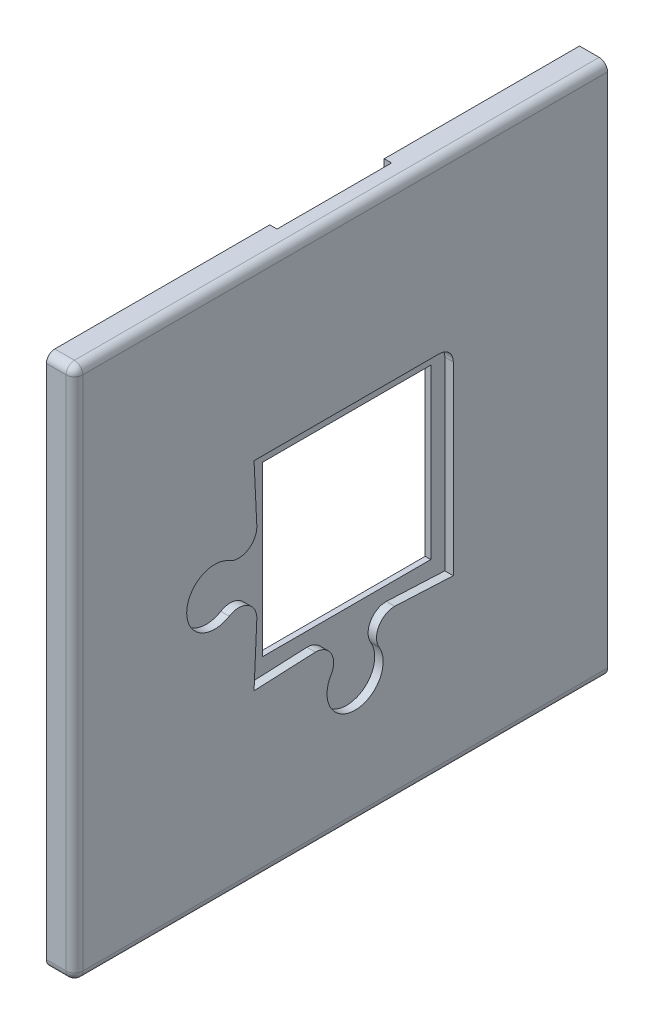
SolidWorks part; units mm, degrees
ref_plane "Front Plane" through (0, 0, 0) normal (0, 0, 1) x (1, 0, 0)
ref_plane "Top Plane" through (0, 0, 0) normal (0, 1, 0) x (1, 0, 0)
ref_plane "Right Plane" through (0, 0, 0) normal (1, 0, 0) x (0, 0, -1)
sketch "Sketch1" plane through (0, 0, 0) normal (1, 0, 0) x (0, 0, -1)
  line L1 (-100, 95) -> (90, 95)
  line L2 (-100, 95) -> (-100, -95)
  line L3 (-100, -95) -> (90, -95)
  line L4 (90, 95) -> (90, -95)
  point P6 (-100, 0)
  dimension "D1" = 190
  dimension "D2" = 190
  dimension "D3" = 100
extrude "Boss-Extrude1" add sketch "Sketch1" along normal blind 10
sketch "Sketch2" plane through (0, 0, 0) normal (-1, 0, 0) x (0, 0, 1)
  line L0 (-35.5, 35.5) -> (-25.5, 35.5)
  line L1 (-35.5, 35.5) -> (-25.5, 35.5)
  line L2 (-35.5, 35.5) -> (-35.5, -35.5)
  line L3 (-35.5, -35.5) -> (35.5, -35.5)
  line L4 (35.5, 35.5) -> (35.5, -35.5)
  line L5 (-25.5, 35.5) -> (-5, 44.5)
  line L6 (-5, 44.5) -> (5, 44.5)
  line L7 (5, 44.5) -> (25.5, 35.5)
  line L8 (25.5, 35.5) -> (35.5, 35.5)
  line L9 (25.5, 35.5) -> (35.5, 35.5)
  line L10 (36.5, 35.5) -> (36.5, -36.5)
  line L11 (-36.5, -36.5) -> (36.5, -36.5)
  line L12 (-36.5, 35.5) -> (-36.5, -36.5)
  line L13 (-35.5, 36.5) -> (-25.5, 36.5)
  line L14 (-25.902, 36.4156) -> (-5.2098, 45.5)
  line L15 (-5.2098, 45.5) -> (5.2098, 45.5)
  line L16 (5.2098, 45.5) -> (25.902, 36.4156)
  line L17 (25.5, 36.5) -> (35.5, 36.5)
  line L18 (-36.5, 35.5) -> (-36.5, 36.5)
  line L19 (-36.5, 36.5) -> (-35.5, 36.5)
  line L20 (35.5, 36.5) -> (36.5, 36.5)
  line L21 (36.5, 36.5) -> (36.5, 35.5)
  point P5 (0, -35.5)
  point P12 (35.5, 0)
  dimension "D1" = 10
  dimension "D2" = 71
  dimension "D3" = 71
  dimension "D4" = 10
  dimension "D5" = 10
  dimension "D6" = 80
  dimension "D7" = 20.5
  dimension "D8" = 1
extrude "Cut-Extrude1" cut sketch "Sketch2" against normal blind 5
sketch "Sketch3" plane through (5, 0, 0) normal (-1, 0, 0) x (0, 0, 1)
  line L1 (-30, 30) -> (30, 30)
  line L2 (-30, 30) -> (-30, -30)
  line L3 (-30, -30) -> (30, -30)
  line L4 (30, 30) -> (30, -30)
  point P4 (0, -30)
  point P6 (30, 0)
  dimension "D1" = 60
  dimension "D2" = 60
extrude "Cut-Extrude2" cut sketch "Sketch3" against normal through all
sketch "Sketch4" plane through (10, 0, 0) normal (1, 0, 0) x (0, 0, -1)
  line L2 (-35, 35) -> (-35, 14.1421) construction
  line L3 (-35, -35) -> (-14.1421, -35) construction
  line L8 (35, 30) -> (35, -35)
  line L9 (36, -36) -> (-36, -36) construction
  line L10 (-36, 37) -> (36, 37) construction
  line L11 (-36, 37) -> (-36, -36) construction
  line L13 (36, 37) -> (36, -36) construction
  line L14 (14.1421, -35) -> (35, -35) construction
  line L15 (30, 35) -> (-35, 35)
  line L16 (-35, -14.1421) -> (-35, -35) construction
  line L17 (-35, 14.1421) -> (-36, 35)
  line L18 (-36, 35) -> (-35, 35)
  line L19 (-14.1421, -35) -> (-36, -36)
  line L20 (-36, -36) -> (-35, -14.1421)
  line L21 (14.1421, -35) -> (35, -36)
  line L22 (35, -36) -> (35, -35)
  arc A6 (-8.571, -44.8485) -> (8.571, -44.8485) centre (0, -50) ccw
  arc A7 (14.1421, -35) -> (8.571, -44.8485) centre (14.1421, -41.5) ccw
  arc A8 (-8.571, -44.8485) -> (-14.1421, -35) centre (-14.1421, -41.5) ccw
  arc A9 (-44.8485, 8.571) -> (-35, 14.1421) centre (-41.5, 14.1421) ccw
  arc A10 (-35, -14.1421) -> (-44.8485, -8.571) centre (-41.5, -14.1421) ccw
  arc A11 (-44.8485, 8.571) -> (-44.8485, -8.571) centre (-50, 0) ccw
  arc A12 (30, 35) -> (35, 30) centre (30, 30) cw
  point P9 (35, 35)
  point P22 (0, 0)
  point P24 (0, 0)
  dimension "D3" = 2
  dimension "D4" = 2
  dimension "D6" = 15
  dimension "D8" = 1
  dimension "D9" = 1
  dimension "D12" = 20
  dimension "D13" = 13
  dimension "D14" = 13
  dimension "D7" = 20.8579
  dimension "D5" = 5
  dimension "D1" = 70
  dimension "D2" = 70
  dimension "D10" = 1
  dimension "D11" = 15
  dimension "D15" = 35
extrude "Cut-Extrude3" cut sketch "Sketch4" against normal blind 3
sketch "Sketch8" plane through (0, 0, 0) normal (-1, 0, 0) x (0, 0, 1)
  line L0 (20, 86) -> (-20, 86) construction
  line L1 (20.4, 98.695) -> (-20.4, 98.695)
  line L2 (20.4, 98.695) -> (20.4, 86.4)
  line L3 (20.4, 86.4) -> (-20.4, 86.4)
  line L4 (-20.4, 98.695) -> (-20.4, 86.4)
  dimension "D1" = 0.4
extrude "Cut-Extrude4" cut sketch "Sketch8" against normal blind 2.6
shell "Shell1" [suppressed] thickness 5
sketch "Sketch9" plane through (0, 0, 0) normal (-1, 0, 0) x (0, 0, 1)
  line L0 (-85, 90) -> (-85, -90)
  line L1 (-85, -90) -> (95, -90)
  line L2 (95, -90) -> (95, 90)
  line L3 (95, 90) -> (25.4, 90)
  line L4 (25.4, 90) -> (25.4, 81.4)
  line L5 (25.4, 81.4) -> (-25.4, 81.4)
  line L6 (-25.4, 81.4) -> (-25.4, 90)
  line L7 (-25.4, 90) -> (-85, 90)
  line L8 (-41.5, 41.5) -> (-41.5, -41.5)
  line L9 (-41.5, -41.5) -> (41.5, -41.5)
  line L10 (41.5, -41.5) -> (41.5, 41.5)
  line L14 (-90, -95) -> (-90, 95) construction
  line L15 (-90, 95) -> (-20.4, 95) construction
  line L16 (-20.4, 95) -> (-20.4, 86.4) construction
  line L17 (20.4, 86.4) -> (20.4, 95) construction
  line L18 (-20.4, 86.4) -> (20.4, 86.4) construction
  line L19 (100, 95) -> (100, -95) construction
  line L20 (100, -95) -> (-90, -95) construction
  line L21 (-36.5, -36.5) -> (-36.5, 36.5) construction
  line L22 (-36.5, -36.5) -> (36.5, -36.5) construction
  line L23 (36.5, 36.5) -> (36.5, -36.5) construction
  line L24 (-5.2098, 45.5) -> (5.2098, 45.5)
  line L27 (-41.5, 41.5) -> (-19.2962, 41.5)
  line L28 (-19.2962, 41.5) -> (-5.6295, 47.5)
  line L29 (-5.6295, 47.5) -> (5.6295, 47.5) construction
  line L30 (5.6295, 47.5) -> (19.2962, 41.5)
  line L32 (19.2962, 41.5) -> (41.5, 41.5)
  line L33 (-36.5, 36.5) -> (-25.7098, 36.5) construction
  line L35 (-25.7098, 36.5) -> (-5.2098, 45.5) construction
  line L36 (5.2098, 45.5) -> (25.7098, 36.5) construction
  line L37 (-5.2098, 45.5) -> (5.2098, 45.5) construction
  line L38 (5.2098, 45.5) -> (25.7098, 36.5) construction
  line L39 (25.7098, 36.5) -> (36.5, 36.5) construction
  line L40 (-25.7098, 36.5) -> (-5.2098, 45.5) construction
  line L41 (-12.5, -41.5) -> (-12.5, -61.5)
  line L42 (-12.5, -61.5) -> (12.5, -61.5)
  line L43 (12.5, -61.5) -> (12.5, -41.5)
  line L44 (41.5, 12.5) -> (61.5, 12.5)
  line L45 (61.5, 12.5) -> (61.5, -12.5)
  line L46 (61.5, -12.5) -> (41.5, -12.5)
  line L47 (-5.2098, 45.5) -> (-5.6295, 47.5)
  line L48 (5.2098, 45.5) -> (5.6295, 47.5)
  point P59 (61.5, 0)
  point P62 (41.5, 0)
  point P63 (0, -61.5)
  point P64 (0, -41.5)
  line M34 (-5.2098, 45.5) -> (5.2098, 45.5)
  dimension "D1" = 5
  dimension "D2" = 5
  dimension "D3" = 5
  dimension "D4" = 5
  dimension "D5" = 5
  dimension "D6" = 5
  dimension "D7" = 5
  dimension "D8" = 5
  dimension "D9" = 5
  dimension "D10" = 5
  dimension "D11" = 5
  dimension "D12" = 5
  dimension "D13" = 2
  dimension "D14" = 2
  dimension "D15" = 5
  dimension "D16" = 2
  dimension "D17" = 25
  dimension "D18" = 25
  dimension "D19" = 20
  dimension "D20" = 20
extrude "Cut-Extrude5" cut sketch "Sketch9" against normal blind 7 contours L6 L7 L0 L1 L2 L3 L4 L5 L45 L46 L10 L9 L43 L42 L41 L8 L27 L28 L29 L30 L32 L44 | L29 L47 L48 M34
fillet "Fillet1" radius 3 5 edges at (5, 95, 100) (5, -95, 100) (10, 95, 5) (10, 0, 100) (10, -95, 5)
sketch "Sketch10" plane through (0, -61.5, 0) normal (0, -1, 0) x (1, 0, 0)
  line L0 (7, -12.5) -> (7, 12.5) construction
  line L1 (2.7, -2.6) -> (5.8, -2.6)
  line L2 (2.7, -2.6) -> (2.7, 2.6)
  line L3 (2.7, 2.6) -> (5.8, 2.6)
  line L4 (5.8, -2.6) -> (5.8, 2.6)
  line L6 (7, -12.5) -> (0, -12.5) construction
  point P8 (2.7, 0)
  dimension "D1" = 5.2
  dimension "D2" = 3.1
  dimension "D3" = 1.2
  dimension "D4" = 12.5
extrude "Cut-Extrude6" cut sketch "Sketch10" against normal blind 15
fillet "Fillet2" radius 1 4 edges at (4.25, -61.5, -2.6) (5.8, -61.5, 0) (4.25, -61.5, 2.6) (2.7, -61.5, 0)
sketch "Sketch11" plane through (0, 0, 61.5) normal (0, 0, 1) x (1, 0, 0)
  line L1 (2.7, 2.6) -> (5.8, 2.6)
  line L2 (2.7, 2.6) -> (2.7, -2.6)
  line L3 (2.7, -2.6) -> (5.8, -2.6)
  line L4 (5.8, 2.6) -> (5.8, -2.6)
  line L5 (7, -12.5) -> (0, -12.5) construction
  line L6 (7, 12.5) -> (7, -12.5) construction
  point P4 (2.7, 0)
  dimension "D1" = 3.1
  dimension "D2" = 5.2
  dimension "D3" = 12.5
  dimension "D4" = 1.2
extrude "Cut-Extrude7" cut sketch "Sketch11" against normal blind 15
fillet "Fillet3" radius 1 4 edges at (2.7, 0, 61.5) (4.25, -2.6, 61.5) (5.8, 0, 61.5) (4.25, 2.6, 61.5)
fillet "Fillet4" radius 4 4 edges at (3.5, 12.5, 61.5) (3.5, -12.5, 61.5) (3.5, -61.5, 12.5) (3.5, -61.5, -12.5)
sketch "Sketch12" plane through (0, 0, 0) normal (-1, 0, 0) x (0, 0, 1)
  line L0 (-85, 90) -> (-85, -90) construction
  line L1 (-85, -79.8) -> (-89, -79.8)
  line L2 (-85, -79.8) -> (-85, -85)
  line L3 (-85, -85) -> (-89, -85)
  line L4 (-89, -79.8) -> (-89, -85)
  line L5 (-90, -95) -> (-90, 95) construction
  line L6 (97, -95) -> (-90, -95) construction
  dimension "D1" = 1
  dimension "D2" = 10
  dimension "D3" = 5.2
extrude "Cut-Extrude8" cut sketch "Sketch12" against normal blind 2
sketch "Sketch13" plane through (2, 0, 0) normal (-1, 0, 0) x (0, 0, 1)
  line L0 (-89, -85) -> (-85, -85) construction
  line L1 (-89, -79.8) -> (-86, -79.8)
  line L2 (-89, -79.8) -> (-89, -85)
  line L3 (-89, -85) -> (-86, -85)
  line L4 (-86, -79.8) -> (-86, -85)
  dimension "D1" = 3
extrude "Cut-Extrude9" cut sketch "Sketch13" against normal blind 6
sketch "Sketch14" plane through (7, 0, 0) normal (-1, 0, 0) x (0, 0, 1)
  line L0 (95, -90) -> (95, 90) construction
  line L1 (95, -77.4) -> (92, -77.4)
  line L2 (95, -77.4) -> (95, -87.4)
  line L3 (95, -87.4) -> (92, -87.4)
  line L4 (92, -77.4) -> (92, -87.4)
  line L5 (-89, -79.8) -> (-89, -85) construction
  point P8 (-89, -82.4)
  point P9 (92, -82.4)
  dimension "D1" = 10
  dimension "D2" = 3
extrude "Boss-Extrude2" add sketch "Sketch14" along normal blind 7
sketch "Sketch16" plane through (0, 0, 92) normal (0, 0, -1) x (-1, 0, 0)
  line L0 (0, -77.4) -> (0, -87.4) construction
  line L1 (-4.4, -79.9) -> (-1.2, -79.9)
  line L2 (-4.4, -79.9) -> (-4.4, -84.9)
  line L3 (-4.4, -84.9) -> (-1.2, -84.9)
  line L4 (-1.2, -79.9) -> (-1.2, -84.9)
  point P6 (0, -82.4)
  point P7 (-1.2, -82.4)
  dimension "D1" = 3.2
  dimension "D2" = 1.2
  dimension "D3" = 5
extrude "Cut-Extrude10" cut sketch "Sketch16" against normal blind 6
fillet "Fillet5" radius 1 3 edges at (2.8, -84.9, 92) (4.4, -82.4, 92) (2.8, -79.9, 92)
sketch "Sketch17" plane through (0, 0, 0) normal (-1, 0, 0) x (0, 0, 1)
  line L1 (-65.5796, 65.977) -> (65.5796, 65.977)
  line L2 (-65.5796, 65.977) -> (-65.5796, -65.977)
  line L3 (-65.5796, -65.977) -> (65.5796, -65.977)
  line L4 (65.5796, 65.977) -> (65.5796, -65.977)
  point P4 (0, 65.977)
  point P6 (-65.5796, 0)
  dimension "D1" = 131.954
  dimension "D2" = 131.1591
extrude "Cut-Extrude11" cut sketch "Sketch17" against normal blind 2.1
sketch "Sketch18" plane through (0, 0, 0) normal (-1, 0, 0) x (0, 0, 1)
  line L0 (97, -95) -> (-90, -95) construction
  line L1 (-90, -95) -> (-90, 95) construction
  line L2 (-90, 95) -> (-20.4, 95) construction
  line L3 (-20.4, 95) -> (-20.4, 86.4) construction
  line L4 (-20.4, 86.4) -> (20.4, 86.4) construction
  line L5 (20.4, 86.4) -> (20.4, 95) construction
  line L6 (20.4, 95) -> (97, 95) construction
  line L7 (100, 92) -> (100, -92) construction
  line L8 (97, -95) -> (-90, -95) construction
  line L9 (-90, -95) -> (-90, 95) construction
  line L10 (-90, 95) -> (-20.4, 95) construction
  line L11 (-20.4, 95) -> (-20.4, 86.4) construction
  line L12 (-20.4, 86.4) -> (20.4, 86.4) construction
  line L13 (20.4, 86.4) -> (20.4, 95) construction
  line L14 (20.4, 95) -> (97, 95) construction
  line L15 (100, 92) -> (100, -92) construction
  line L16 (-87, 92) -> (-23.4, 92)
  line L17 (-23.4, 92) -> (-23.4, 83.4)
  line L18 (-23.4, 83.4) -> (23.4, 83.4)
  line L19 (23.4, 83.4) -> (23.4, 92)
  line L20 (23.4, 92) -> (97, 92)
  line L21 (97, 92) -> (97, -92)
  line L22 (97, -92) -> (-87, -92)
  line L23 (-87, -92) -> (-87, 92)
  line L24 (92, -87.4) -> (97, -87.4)
  line L25 (97, -87.4) -> (97, -77.4)
  line L26 (97, -77.4) -> (92, -77.4)
  line L27 (92, -77.4) -> (92, -87.4)
  line L28 (95, -77.4) -> (92, -77.4) construction
  arc A0 (97, -95) -> (100, -92) centre (97, -92) ccw construction
  arc A1 (100, 92) -> (97, 95) centre (97, 92) ccw construction
  arc A2 (97, -95) -> (100, -92) centre (97, -92) ccw construction
  arc A3 (100, 92) -> (97, 95) centre (97, 92) ccw construction
  arc A4 (97, 92) -> (97, 92) centre (97, 92) ccw
  arc A5 (97, -92) -> (97, -92) centre (97, -92) ccw
  line M19 (-85, -90) -> (-85, -85)
  line M20 (-85, -85) -> (-89, -85)
  line M22 (-89, -79.8) -> (-85, -79.8)
  line M23 (-85, -79.8) -> (-85, 90)
  line M24 (-85, 90) -> (-25.4, 90)
  line M25 (-25.4, 90) -> (-25.4, 81.4)
  line M26 (-25.4, 81.4) -> (25.4, 81.4)
  line M27 (25.4, 81.4) -> (25.4, 90)
  line M28 (25.4, 90) -> (95, 90)
  line M29 (95, 90) -> (95, -77.4)
  line M30 (95, -77.4) -> (92, -77.4)
  line M31 (92, -77.4) -> (92, -87.4)
  line M32 (92, -87.4) -> (95, -87.4)
  line M33 (95, -87.4) -> (95, -90)
  line M34 (95, -90) -> (-85, -90)
  dimension "D1" = 3
extrude "Cut-Extrude12" cut sketch "Sketch18" against normal blind 2 contours L26 L21 L20 L19 L18 L17 L16 L23 M22 M23 M24 M25 M26 M27 M28 M29 | L23 M20 M19 M34 M33 M32 M31 M30 M29 M28 M27 M26 M25 M24 M23 M22 | L24 L23 L22 L21 M33 M34 M19 M20
